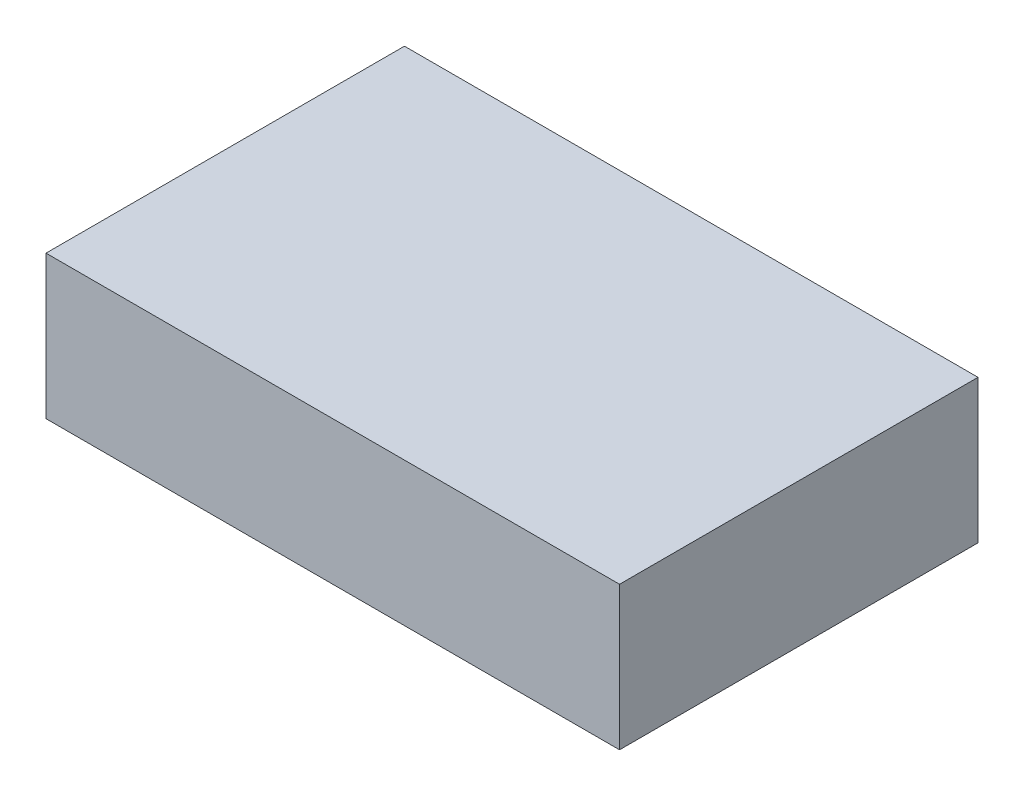
SolidWorks part; units mm, degrees
ref_plane "Front Plane" through (0, 0, 0) normal (0, 0, 1) x (1, 0, 0)
ref_plane "Top Plane" through (0, 0, 0) normal (0, 1, 0) x (1, 0, 0)
ref_plane "Right Plane" through (0, 0, 0) normal (1, 0, 0) x (0, 0, -1)
sketch "Sketch1" plane through (0, 0, 0) normal (0, 1, 0) x (1, 0, 0)
  line L1 (-50.8, 25.4) -> (50.8, 25.4)
  line L2 (-50.8, 25.4) -> (-50.8, -38.1)
  line L3 (-50.8, -38.1) -> (50.8, -38.1)
  line L4 (50.8, 25.4) -> (50.8, -38.1)
  point P0 (0, 0)
  dimension "D1" = 101.6
  dimension "D2" = 63.5
extrude "Extrude1" add sketch "Sketch1" against normal blind 25.4
sketch "Sketch2" plane through (0, 0, 0) normal (0, 1, 0) x (1, 0, 0)
  line L0 (0, 0) -> (-41.275, 0) construction
  dimension "D1" = 9.525
ref_plane "Plane1" through (-41.275, 0, 0) normal (-1, 0, 0) x (0, 0, 1)
sketch "Sketch3" plane through (-41.275, 0, 0) normal (-1, 0, 0) x (0, 0, 1)
  line L1 (-9.5123, 4.7625) -> (9.5489, 4.7625)
  line L2 (-11.1125, 3.1623) -> (-11.1125, -3.1623)
  line L3 (-9.5123, -4.7625) -> (9.5489, -4.7625)
  line L4 (11.1491, 3.1623) -> (11.1491, -3.1623)
  arc A0 (-9.5123, 4.7625) -> (-11.1125, 3.1623) centre (-9.5123, 3.1623) ccw
  arc A1 (-11.1125, -3.1623) -> (-9.5123, -4.7625) centre (-9.5123, -3.1623) ccw
  arc A2 (9.5489, -4.7625) -> (11.1491, -3.1623) centre (9.5489, -3.1623) ccw
  arc A3 (9.5489, 4.7625) -> (11.1491, 3.1623) centre (9.5489, 3.1623) cw
  point P0 (0, 0)
  point P8 (-11.0759, 4.7625)
  point P13 (11.1491, -4.7625)
  point P16 (11.1491, 4.7625)
  point P17 (-11.1125, 0)
  point P18 (11.1491, 0)
  dimension "D3" = 1.6002
  dimension "D1" = 22.225
  dimension "D2" = 9.525
sketch "Sketch4" plane through (0, 0, 0) normal (0, 1, 0) x (1, 0, 0)
  line L0 (-41.275, 11.1125) -> (-41.275, -14.2875) construction
  line L1 (-41.275, -14.2875) -> (34.925, -14.2875) construction
  dimension "D1" = 25.4
  dimension "D2" = 76.2
sketch "Sketch5" plane through (0, 0, 0) normal (0, 1, 0) x (-1, 0, 0)
  arc A0 (41.275, -11.1125) -> (-34.925, 14.2875) centre (27.8781, 75.6968) cw
ref_plane "Plane2" through (34.925, 0, 14.2875) normal (0.6991, 0, 0.715) x (0.715, 0, -0.6991)
sketch "Sketch6" plane through (34.925, 0, 14.2875) normal (0.6991, 0, 0.715) x (0.715, 0, -0.6991)
  line L0 (-24.0792, 0) -> (0, 0) construction
  line L1 (0, -2.9956) -> (0, 2.9956)
  line L2 (-24.0792, -3.7936) -> (-24.0792, 3.7936) construction
  arc A0 (-23.8052, -3.9988) -> (-0.6869, -4.3095) centre (-12.0288, 12.0083) ccw
  arc A1 (-24.2643, 3.4714) -> (-24.2643, -3.4714) centre (-17.849, 0) ccw
  arc A3 (-0.6869, 4.3095) -> (0, 2.9956) centre (-1.6002, 2.9956) cw
  arc A4 (-0.6869, -4.3095) -> (0, -2.9956) centre (-1.6002, -2.9956) ccw
  arc A5 (-23.8052, 3.9988) -> (-0.6869, 4.3095) centre (-12.0288, -12.0083) cw
  arc A6 (-23.8052, 3.9988) -> (-24.2643, 3.4714) centre (-22.8569, 2.7099) ccw
  arc A7 (-23.8052, -3.9988) -> (-24.2643, -3.4714) centre (-22.8569, -2.7099) cw
  point P0 (-12.0396, 0)
  point P12 (0, 3.81)
  point P15 (0, -3.81)
  point P18 (-24.0792, 3.7936)
  point P21 (-24.0792, -3.7936)
  point P26 (-25.1433, 0)
  point P27 (-36.8447, 6.6142)
  point P29 (-32.8967, 8.4939)
  dimension "D3" = 1.6002
  dimension "D4" = 1.6002
  dimension "D1" = 24.0792
  dimension "D2" = 7.62
sketch "Sketch7" plane through (0, 0, 0) normal (0, 1, 0) x (1, 0, 0)
  arc A0 (-41.275, 0) -> (26.6636, -22.9903) centre (-37.424, -100.4978) cw
sketch "Sketch9" plane through (0, 0, 0) normal (0, 1, 0) x (1, 0, 0)
  line L0 (-41.275, -11.1491) -> (-38.0236, -11.1678)
  arc A0 (-37.6694, -11.1797) -> (-33.2091, -11.5349) centre (-45.3772, -136.1664) cw
  arc A1 (-29.312, -13.3889) -> (-16.8006, -14.7066) centre (-22.2511, -6.4033) ccw
  arc A2 (-16.8006, -14.7066) -> (-4.1713, -20.4225) centre (-13.3432, -23.8777) cw
  arc A3 (-4.1713, -20.4225) -> (6.8712, -25.8342) centre (4.7287, -16.234) ccw
  arc A5 (-29.312, -13.3889) -> (-33.2091, -11.5349) centre (-33.8261, -17.8548) ccw
  arc A6 (6.8712, -25.8342) -> (11.8418, -26.7922) centre (8.2544, -32.0317) cw
  arc A7 (-38.0236, -11.1678) -> (-37.6694, -11.1797) centre (-38.0602, -17.5177) cw
  arc A8 (16.9476, -31.8659) -> (11.8418, -26.7922) centre (0.6002, -43.211) ccw
  point P19 (7.3055, -22.5635)
  dimension "D1" = 6.35
  dimension "D2" = 6.35
